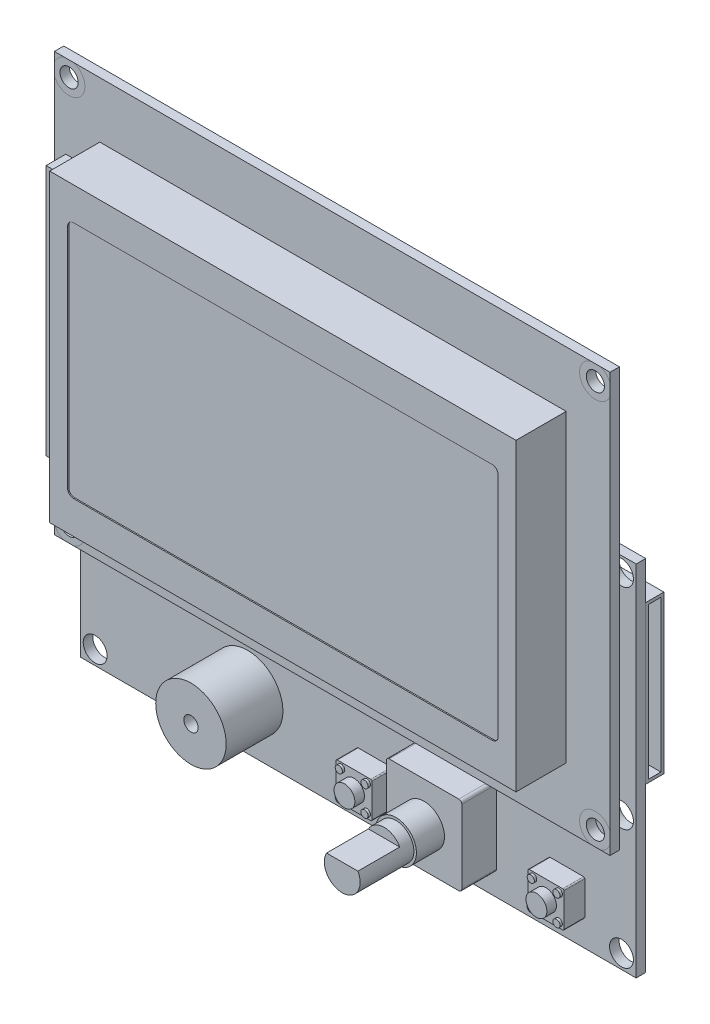
SolidWorks part; units mm, degrees
ref_plane "Ön Düzlem" through (0, 0, 0) normal (0, 0, 1) x (1, 0, 0)
ref_plane "Üst Düzlem" through (0, 0, 0) normal (0, 1, 0) x (1, 0, 0)
ref_plane "Sağ Düzlem" through (0, 0, 0) normal (1, 0, 0) x (0, 0, -1)
sketch "Sketch1" plane through (0, 0, 0) normal (0, 0, 1) x (1, 0, 0)
  line L1 (0, 0) -> (93.06, 0)
  line L2 (0, 0) -> (0, 70.1)
  line L3 (0, 70.1) -> (93.06, 70.1)
  line L4 (93.06, 0) -> (93.06, 70.1)
  line L5 (2.455, 67.565) -> (90.605, 67.565) construction
  line L6 (2.455, 67.565) -> (2.455, 2.535) construction
  line L7 (2.455, 2.535) -> (90.605, 2.535) construction
  line L8 (90.605, 67.565) -> (90.605, 2.535) construction
  circle A0 centre (2.455, 67.565) radius 1.525
  circle A1 centre (90.605, 67.565) radius 1.525
  circle A2 centre (90.605, 2.535) radius 1.525
  circle A3 centre (2.455, 2.535) radius 1.525
  dimension "D1" = 93.06
  dimension "D2" = 70.1
  dimension "D3" = 88.15
  dimension "D4" = 65.03
  dimension "D5" = 2.535
  dimension "D6" = 2.455
extrude "Boss-Extrude1" add sketch "Sketch1" along normal blind 1.57
sketch "Sketch2" plane through (0, 0, 1.57) normal (0, 0, 1) x (1, 0, 0)
  line L0 (93.06, 70.1) -> (0, 70.1) construction
  line L1 (7.61, 60.75) -> (85.71, 60.75)
  line L2 (7.61, 60.75) -> (7.61, 9.75)
  line L3 (7.61, 9.75) -> (85.71, 9.75)
  line L4 (85.71, 60.75) -> (85.71, 9.75)
  line L5 (93.06, 0) -> (93.06, 70.1) construction
  dimension "D1" = 51
  dimension "D2" = 78.1
  dimension "D3" = 9.35
  dimension "D4" = 7.35
extrude "Boss-Extrude2" add sketch "Sketch2" along normal blind 8.4
sketch "Sketch3" plane through (0, 0, 9.97) normal (0, 0, 1) x (1, 0, 0)
  line L0 (85.71, 60.75) -> (7.61, 60.75) construction
  line L1 (11.61, 55.25) -> (81.71, 55.25)
  line L2 (10.61, 54.25) -> (10.61, 16.25)
  line L3 (11.61, 15.25) -> (81.71, 15.25)
  line L4 (82.71, 54.25) -> (82.71, 16.25)
  line L5 (7.61, 9.75) -> (85.71, 9.75) construction
  line L6 (7.61, 60.75) -> (7.61, 9.75) construction
  line L7 (85.71, 9.75) -> (85.71, 60.75) construction
  arc A0 (10.61, 16.25) -> (11.61, 15.25) centre (11.61, 16.25) ccw
  arc A1 (81.71, 15.25) -> (82.71, 16.25) centre (81.71, 16.25) ccw
  arc A2 (81.71, 55.25) -> (82.71, 54.25) centre (81.71, 54.25) cw
  arc A3 (11.61, 55.25) -> (10.61, 54.25) centre (11.61, 54.25) ccw
  dimension "D5" = 1
  dimension "D1" = 5.5
  dimension "D2" = 5.5
  dimension "D3" = 3
  dimension "D4" = 3
extrude "Cut-Extrude1" cut sketch "Sketch3" against normal blind 0.2
sketch "Sketch4" plane through (0, 0, 1.57) normal (0, 0, 1) x (1, 0, 0)
  line L0 (7.61, 60.75) -> (7.61, 9.75) construction
  line L1 (1.91, 56.15) -> (7.61, 56.15)
  line L2 (1.91, 56.15) -> (1.91, 14.05)
  line L3 (1.91, 14.05) -> (7.61, 14.05)
  line L4 (7.61, 56.15) -> (7.61, 14.05)
  line L5 (85.71, 60.75) -> (7.61, 60.75) construction
  dimension "D1" = 5.7
  dimension "D2" = 42.1
  dimension "D3" = 4.6
extrude "Boss-Extrude3" add sketch "Sketch4" along normal blind 3.3
sketch "Sketch5" plane through (0, 0, 1.57) normal (0, 0, 1) x (1, 0, 0)
  circle A0 centre (2.455, 67.565) radius 2.65
  circle A1 centre (90.605, 67.565) radius 2.65
  circle A2 centre (90.605, 2.535) radius 2.65
  circle A3 centre (2.455, 2.535) radius 2.65
split line "Split Line1"
ref_plane "Plane1" through (0, 0, -2.8) normal (0, 0, -1) x (-1, 0, 0)
sketch "Sketch6" plane through (0, 0, -2.8) normal (0, 0, -1) x (-1, 0, 0)
  line L0 (0, 0) -> (-93.06, 0) construction
  line L1 (-93.06, 40.1) -> (0, 40.1)
  line L2 (-93.06, 40.1) -> (-93.06, -19.95)
  line L3 (-93.06, -19.95) -> (0, -19.95)
  line L4 (0, 40.1) -> (0, -19.95)
  line L5 (-93.06, 0) -> (-93.06, 70.1) construction
  line L6 (0, 70.1) -> (0, 0) construction
  dimension "D1" = 19.95
  dimension "D2" = 60.05
extrude "Boss-Extrude4" add sketch "Sketch6" along normal blind 1.6 separate body
sketch "Sketch7" plane through (0, 0, -4.4) normal (0, 0, -1) x (-1, 0, 0)
  circle A0 centre (-90.605, 37.685) radius 2
  circle A1 centre (-90.605, -17.565) radius 2
  circle A2 centre (-2.455, -17.565) radius 2
  circle A3 centre (-2.455, 37.685) radius 2
  circle A4 centre (-90.605, 2.535) radius 2
  circle A5 centre (-2.455, 2.535) radius 2
  dimension "D1" = 55.25
  dimension "D2" = 55.25
  dimension "D3" = 20.1
  dimension "D4" = 20.1
  dimension "D5" = 4
  dimension "D6" = 4
  dimension "D7" = 4
  dimension "D8" = 4
  dimension "D9" = 4
  dimension "D10" = 4
extrude "Cut-Extrude2" cut sketch "Sketch7" against normal blind 1.6
sketch "Sketch8" plane through (0, 0, 0) normal (0, 0, -1) x (-1, 0, 0)
  line L0 (-93.06, 40.1) -> (-93.06, -19.95) construction
  line L1 (-83.06, 10) -> (-10, 10)
  line L2 (-83.06, 10) -> (-83.06, 12)
  line L3 (-83.06, 30.1) -> (-10, 30.1)
  line L4 (-10, 10) -> (-10, 12)
  line L5 (-83.06, 12) -> (-10, 12)
  line L7 (-83.06, 28.1) -> (-10, 28.1)
  line L9 (0, -19.95) -> (0, 40.1) construction
  line L10 (0, 40.1) -> (-93.06, 40.1) construction
  line L11 (0, 0) -> (-93.06, 0) construction
  line L12 (-83.06, 28.1) -> (-83.06, 30.1)
  line L13 (-10, 28.1) -> (-10, 30.1)
  dimension "D1" = 10
  dimension "D2" = 10
  dimension "D3" = 10
  dimension "D4" = 2
  dimension "D5" = 2
  dimension "D6" = 10
extrude "Boss-Extrude5" add sketch "Sketch8" along normal up to next
sketch "Sketch9" plane through (0, 0, -4.4) normal (0, 0, -1) x (-1, 0, 0)
  line L0 (0, -19.95) -> (0, 40.1) construction
  line L1 (-47.8, 38.45) -> (-27.5, 38.45)
  line L2 (-47.8, 38.45) -> (-47.8, 29.7)
  line L3 (-47.8, 29.7) -> (-27.5, 29.7)
  line L4 (-27.5, 38.45) -> (-27.5, 29.7)
  line L5 (-26.8, 38.45) -> (-6.5, 38.45)
  line L6 (-26.8, 38.45) -> (-26.8, 29.7)
  line L7 (-26.8, 29.7) -> (-6.5, 29.7)
  line L8 (-6.5, 38.45) -> (-6.5, 29.7)
  line L9 (0, 40.1) -> (-93.06, 40.1) construction
  line L10 (-47.3, 30.2) -> (-28, 30.2)
  line L11 (-28, 37.95) -> (-28, 30.2)
  line L12 (-47.3, 37.95) -> (-28, 37.95)
  line L13 (-47.3, 37.95) -> (-47.3, 30.2)
  line L14 (-26.3, 30.2) -> (-7, 30.2)
  line L15 (-7, 37.95) -> (-7, 30.2)
  line L16 (-26.3, 37.95) -> (-7, 37.95)
  line L17 (-26.3, 37.95) -> (-26.3, 30.2)
  dimension "D1" = 8.75
  dimension "D2" = 8.75
  dimension "D3" = 20.3
  dimension "D4" = 20.3
  dimension "D5" = 41.3
  dimension "D6" = 6.5
  dimension "D7" = 1.65
  dimension "D8" = 1.65
  dimension "D9" = 0.5
  dimension "D10" = 0.5
extrude "Boss-Extrude6" add sketch "Sketch9" along normal blind 9 contours L4 L1 L2 L3 L13 L12 L11 L10 | L8 L5 L6 L7 L17 L16 L15 L14
sketch "Sketch10" plane through (0, 0, -4.4) normal (0, 0, -1) x (-1, 0, 0)
  line L0 (-93.06, 33.7) -> (-66.46, 33.7)
  line L1 (-93.06, 40.1) -> (-93.06, -19.95) construction
  line L2 (-66.46, 33.7) -> (-66.46, 9.35)
  line L3 (-66.46, 9.35) -> (-71.86, 9.35)
  line L4 (-71.86, 9.35) -> (-75.06, 7.35)
  line L5 (-75.06, 7.35) -> (-93.06, 7.35)
  line L6 (-93.06, 7.35) -> (-93.06, 33.7)
  line L7 (0, 40.1) -> (-93.06, 40.1) construction
  dimension "D1" = 26.35
  dimension "D2" = 6.4
  dimension "D3" = 18
  dimension "D4" = 26.6
  dimension "D5" = 2
  dimension "D6" = 5.4
extrude "Boss-Extrude7" add sketch "Sketch10" along normal blind 3.05
sketch "Sketch11" plane through (93.06, 0, 0) normal (1, 0, 0) x (0, 0, -1)
  line L0 (7.45, 33.7) -> (7.45, 7.35) construction
  line L1 (4.9, 33.2) -> (6.95, 33.2)
  line L2 (4.9, 33.2) -> (4.9, 7.85)
  line L3 (4.9, 7.85) -> (6.95, 7.85)
  line L4 (6.95, 33.2) -> (6.95, 7.85)
  line L5 (7.45, 7.35) -> (4.4, 7.35) construction
  line L6 (7.45, 33.7) -> (4.4, 33.7) construction
  line L7 (4.4, 38.45) -> (4.4, 29.7) construction
  dimension "D1" = 0.5
  dimension "D2" = 0.5
  dimension "D3" = 0.5
  dimension "D4" = 0.5
extrude "Cut-Extrude3" cut sketch "Sketch11" against normal up to next
sketch "Sketch12" plane through (0, 0, -7.45) normal (0, 0, -1) x (-1, 0, 0)
  line L2 (-75.06, 7.35) -> (-71.86, 9.35)
  line L3 (-71.86, 9.35) -> (-66.46, 9.35)
  line L4 (-66.46, 9.35) -> (-66.46, 33.7)
  line L5 (-66.46, 33.7) -> (-66.96, 33.7)
  line L6 (-66.46, 33.7) -> (-93.06, 33.7) construction
  line L7 (-66.96, 33.7) -> (-66.96, 9.85)
  line L8 (-66.96, 9.85) -> (-72.0034, 9.85)
  line L9 (-72.0034, 9.85) -> (-75.2034, 7.85)
  line L10 (-75.2034, 7.85) -> (-77.7784, 7.85)
  line L11 (-77.7784, 7.85) -> (-77.7784, 7.35)
  line L12 (-93.06, 7.35) -> (-75.06, 7.35) construction
  line L13 (-77.7784, 7.35) -> (-75.06, 7.35)
  dimension "D1" = 0.5
  dimension "D2" = 0.5
  dimension "D3" = 0.5
  dimension "D4" = 0.5
extrude "Boss-Extrude8" add sketch "Sketch12" against normal blind 3.05
sketch "Sketch13" plane through (93.06, 0, 0) normal (1, 0, 0) x (0, 0, -1)
  line L0 (4.4, 33.7) -> (4.4, 7.35)
split line "Split Line2"
sketch "Sketch14" plane through (0, 0, -2.8) normal (0, 0, 1) x (1, 0, 0)
  line L0 (93.06, -19.95) -> (0, -19.95) construction
  line L1 (78.66, -9.65) -> (84.26, -9.65)
  line L2 (78.46, -9.85) -> (78.46, -15.45)
  line L3 (78.66, -15.65) -> (84.26, -15.65)
  line L4 (84.46, -9.85) -> (84.46, -15.45)
  line L5 (46.51, -9.85) -> (52.11, -9.85)
  line L6 (46.31, -10.05) -> (46.31, -15.65)
  line L7 (46.51, -15.85) -> (52.11, -15.85)
  line L8 (52.31, -10.05) -> (52.31, -15.65)
  line L9 (93.06, 40.1) -> (93.06, -19.95) construction
  arc A0 (78.46, -15.45) -> (78.66, -15.65) centre (78.66, -15.45) ccw
  arc A1 (84.26, -15.65) -> (84.46, -15.45) centre (84.26, -15.45) ccw
  arc A2 (84.26, -9.65) -> (84.46, -9.85) centre (84.26, -9.85) cw
  arc A3 (78.66, -9.65) -> (78.46, -9.85) centre (78.66, -9.85) ccw
  arc A4 (52.11, -15.85) -> (52.31, -15.65) centre (52.11, -15.65) ccw
  arc A5 (46.31, -15.65) -> (46.51, -15.85) centre (46.51, -15.65) ccw
  arc A6 (46.51, -9.85) -> (46.31, -10.05) centre (46.51, -10.05) ccw
  arc A7 (52.11, -9.85) -> (52.31, -10.05) centre (52.11, -10.05) cw
  point P14 (78.46, -15.65)
  point P19 (84.46, -9.65)
  point P22 (78.46, -9.65)
  point P25 (52.31, -15.85)
  point P30 (46.31, -9.85)
  point P33 (52.31, -9.85)
  dimension "D9" = 0.2
  dimension "D1" = 4.3
  dimension "D2" = 4.1
  dimension "D3" = 8.6
  dimension "D4" = 6
  dimension "D5" = 6
  dimension "D6" = 6
  dimension "D7" = 6
  dimension "D8" = 38.15
extrude "Boss-Extrude9" add sketch "Sketch14" along normal blind 3.5
sketch "Sketch15" plane through (0, 0, 0.7) normal (0, 0, 1) x (1, 0, 0)
  line L0 (52.11, -9.85) -> (46.51, -9.85) construction
  line L1 (46.31, -10.05) -> (46.31, -15.65) construction
  line L2 (84.26, -9.65) -> (78.66, -9.65) construction
  line L3 (78.46, -9.85) -> (78.46, -15.45) construction
  circle A0 centre (49.31, -12.85) radius 1.75
  circle A1 centre (81.46, -12.65) radius 1.75
  dimension "D1" = 3.5
  dimension "D2" = 3.5
  dimension "D3" = 3
  dimension "D4" = 3
  dimension "D5" = 3
  dimension "D6" = 3
extrude "Boss-Extrude10" add sketch "Sketch15" along normal blind 1.6
sketch "Sketch16" plane through (0, 0, -2.8) normal (0, 0, 1) x (1, 0, 0)
  line L0 (93.06, -19.95) -> (0, -19.95) construction
  line L1 (57.51, -3.05) -> (69.16, -3.05)
  line L2 (57.01, -3.55) -> (57.01, -15.85)
  line L3 (57.51, -16.35) -> (69.16, -16.35)
  line L4 (69.66, -3.55) -> (69.66, -15.85)
  line L5 (78.46, -9.85) -> (78.46, -15.45) construction
  arc A0 (57.01, -15.85) -> (57.51, -16.35) centre (57.51, -15.85) ccw
  arc A1 (69.16, -16.35) -> (69.66, -15.85) centre (69.16, -15.85) ccw
  arc A2 (69.16, -3.05) -> (69.66, -3.55) centre (69.16, -3.55) cw
  arc A3 (57.51, -3.05) -> (57.01, -3.55) centre (57.51, -3.55) ccw
  point P12 (69.66, -16.35)
  point P15 (69.66, -3.05)
  point P18 (57.01, -3.05)
  dimension "D5" = 0.5
  dimension "D1" = 13.3
  dimension "D2" = 12.65
  dimension "D3" = 3.6
  dimension "D4" = 8.8
extrude "Boss-Extrude11" add sketch "Sketch16" along normal blind 5.8
sketch "Sketch17" plane through (0, 0, 3) normal (0, 0, 1) x (1, 0, 0)
  line L0 (69.66, -15.85) -> (69.66, -3.55) construction
  line L1 (57.51, -16.35) -> (69.16, -16.35) construction
  circle A0 centre (63.335, -9.7) radius 3.425
  dimension "D1" = 6.85
  dimension "D2" = 6.325
  dimension "D3" = 6.65
extrude "Boss-Extrude12" add sketch "Sketch17" along normal blind 4.7
sketch "Sketch18" plane through (0, 0, 7.7) normal (0, 0, 1) x (1, 0, 0)
  line L0 (60.7087, -8.25) -> (65.9613, -8.25)
  arc A0 (60.7087, -8.25) -> (65.9613, -8.25) centre (63.335, -9.7) ccw
  dimension "D1" = 6
  dimension "D2" = 1.45
extrude "Boss-Extrude13" add sketch "Sketch18" along normal blind 9
sketch "Sketch19" plane through (0, 0, 0.7) normal (0, 0, 1) x (1, 0, 0)
  line L0 (84.46, -15.45) -> (84.46, -9.85) construction
  line L1 (78.66, -15.65) -> (84.26, -15.65) construction
  line L2 (46.31, -10.05) -> (46.31, -15.65) construction
  line L3 (52.31, -15.65) -> (52.31, -10.05) construction
  line L4 (46.51, -15.85) -> (52.11, -15.85) construction
  line L5 (52.11, -9.85) -> (46.51, -9.85) construction
  circle A0 centre (79.31, -10.5) radius 0.6
  circle A1 centre (83.61, -10.5) radius 0.6
  circle A2 centre (83.61, -14.8) radius 0.6
  circle A3 centre (79.31, -14.8) radius 0.6
  circle A4 centre (47.16, -10.7) radius 0.6
  circle A5 centre (51.46, -10.7) radius 0.6
  circle A6 centre (51.46, -15) radius 0.6
  circle A7 centre (47.16, -15) radius 0.6
  dimension "D1" = 4.3
  dimension "D2" = 4.3
  dimension "D3" = 0.85
  dimension "D4" = 0.85
  dimension "D5" = 1.2
  dimension "D6" = 1.2
  dimension "D7" = 1.2
  dimension "D8" = 1.2
  dimension "D9" = 0.85
  dimension "D10" = 0.85
  dimension "D11" = 0.85
  dimension "D12" = 0.85
  dimension "D13" = 1.2
  dimension "D14" = 1.2
  dimension "D15" = 1.2
  dimension "D16" = 1.2
extrude "Boss-Extrude14" add sketch "Sketch19" along normal blind 0.4
sketch "Sketch21" plane through (0, 0, -2.8) normal (0, 0, 1) x (1, 0, 0)
  line L0 (93.06, -19.95) -> (0, -19.95) construction
  line L1 (0, -19.95) -> (0, 40.1) construction
  circle A0 centre (28, -10.85) radius 5.9
  dimension "D1" = 11.8
  dimension "D2" = 9.1
  dimension "D3" = 28
extrude "Boss-Extrude15" add sketch "Sketch21" along normal blind 9.5
sketch "Sketch22" plane through (0, 0, 6.7) normal (0, 0, 1) x (1, 0, 0)
  circle A0 centre (28, -10.85) radius 1.2
extrude "Cut-Extrude4" cut sketch "Sketch22" against normal blind 2
sketch "Sketch23" plane through (0, 0, 7.7) normal (0, 0, 1) x (1, 0, 0)
  circle A0 centre (63.335, -9.7) radius 3
extrude "Boss-Extrude16" add sketch "Sketch23" along normal blind 2
equation "\"D5@Sketch1\"=(\"D2@Sketch1\"-\"D4@Sketch1\")/2"
equation "\"D6@Sketch1\"=(\"D1@Sketch1\"-\"D3@Sketch1\")/2"
